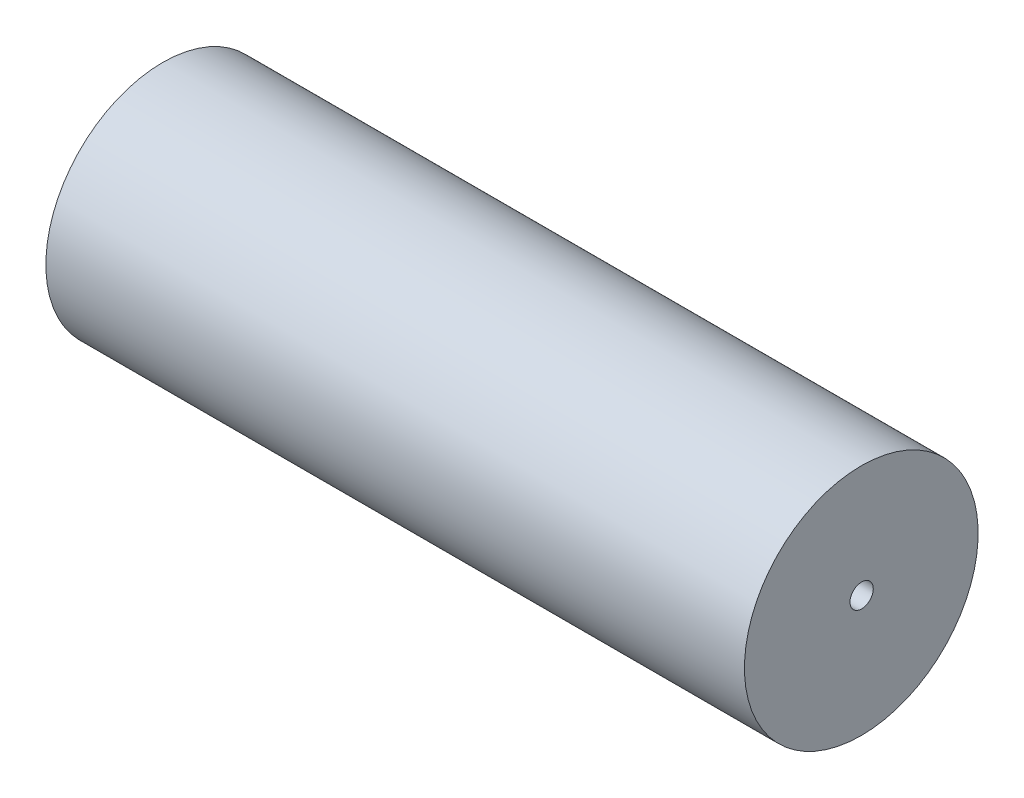
SolidWorks part; units mm, degrees
ref_plane "Front Plane" through (0, 0, 0) normal (0, 0, 1) x (1, 0, 0)
ref_plane "Top Plane" through (0, 0, 0) normal (0, 1, 0) x (1, 0, 0)
ref_plane "Right Plane" through (0, 0, 0) normal (1, 0, 0) x (0, 0, -1)
sketch "Sketch1" plane through (0, 0, 0) normal (0, 0, 1) x (1, 0, 0)
  line L0 (24.9142, 0.1119) -> (-35.0858, 0.1119)
  line L1 (-35.0858, 10.1477) -> (-35.0858, 0.1119)
  line L2 (-35.0858, 10.1477) -> (24.9142, 10.1477)
  line L3 (24.9142, 0.1119) -> (24.9142, 10.1477)
  point P4 (-5.0858, 0.1119)
  point P7 (-35.0858, 5.1298)
  point P8 (0, 0)
  point P9 (0, 0)
revolve "Revolve1" add sketch "Sketch1" angle 360 about L2
sketch "Sketch2" plane through (24.9142, 0, 0) normal (1, 0, 0) x (0, 0, -1)
  circle A1 centre (0.0289, 10.5231) radius 1
extrude "Cut-Extrude1" cut sketch "Sketch2" against normal through all both and the other way through all
